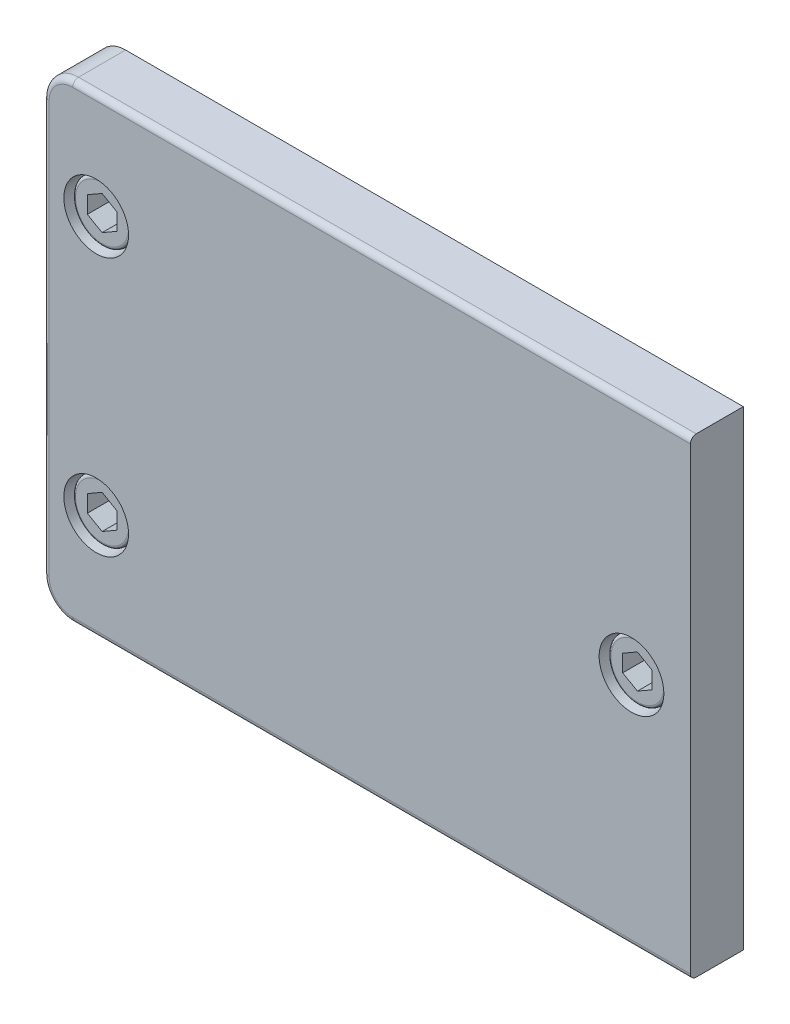
SolidWorks part; units mm, degrees
ref_plane "Plan de face" through (0, 0, 0) normal (0, 0, 1) x (1, 0, 0)
ref_plane "Plan de dessus" through (0, 0, 0) normal (0, 1, 0) x (1, 0, 0)
ref_plane "Plan de droite" through (0, 0, 0) normal (1, 0, 0) x (0, 0, -1)
sketch "Esquisse1" plane through (0, 0, 0) normal (0, 0, 1) x (-1, 0, 0)
  line L8 (0, 5) -> (0, 75)
  line L9 (-5, 80) -> (-110, 80)
  line L10 (-110, 80) -> (-110, 0)
  line L11 (-110, 0) -> (-5, 0)
  arc A4 (0, 75) -> (-5, 80) centre (-5, 75) ccw
  arc A5 (-5, 0) -> (0, 5) centre (-5, 5) ccw
extrude "Boss.-Extru.1" add sketch "Esquisse1" along normal blind 9
fillet "Congé1" radius 1 5 edges at (57.5, -80, 9) (1.4645, -78.5355, 9) (0, -40, 9) (57.5, 0, 9) (1.4645, -1.4645, 9)
sketch "Esquisse2" plane through (0, 0, 0) normal (0, 0, -1) x (1, 0, 0)
  circle A2 centre (9, 18) radius 3.3235
  circle A3 centre (6, 40) radius 3
  circle A4 centre (9, 62) radius 3.3235
  circle A5 centre (50, 40) radius 38
  circle A6 centre (100, 40) radius 3.3235
sketch "Esquisse4" plane through (0, 0, 9) normal (0, 0, 1) x (1, 0, 0)
  circle A0 centre (9, -18) radius 5.5
  dimension "D1" = 11
extrude "Enlèv. mat.-Extru.1" cut sketch "Esquisse4" against normal blind 7
sketch "Esquisse5" plane through (0, 0, 2) normal (0, 0, 1) x (1, 0, 0)
  circle A0 centre (9, -18) radius 5
  dimension "D1" = 10
extrude "Boss.-Extru.2" add sketch "Esquisse5" along normal blind 6
fillet "Congé2" radius 0.5 1 edges at (14, -18, 8)
sketch "Esquisse6" plane through (0, 0, 8) normal (0, 0, 1) x (1, 0, 0)
  line L0 (9, -15.1132) -> (9, -20.8868) construction
  line L1 (9, -15.1132) -> (6.5, -16.5566)
  line L2 (6.5, -16.5566) -> (6.5, -19.4434)
  line L3 (6.5, -19.4434) -> (9, -20.8868)
  line L4 (9, -20.8868) -> (11.5, -19.4434)
  line L5 (11.5, -19.4434) -> (11.5, -16.5566)
  line L6 (11.5, -16.5566) -> (9, -15.1132)
  circle A0 centre (9, -18) radius 2.5 construction
  dimension "D1" = 5
extrude "Enlèv. mat.-Extru.2" cut sketch "Esquisse6" against normal blind 4
pattern_linear "Répétition linéaire1" count 2 spacing 44 along (0, -1, 0) of "Enlèv. mat.-Extru.1", "Boss.-Extru.2", "Congé2", "Enlèv. mat.-Extru.2"
sketch "Esquisse7" plane through (0, 0, 9) normal (0, 0, 1) x (1, 0, 0)
  circle A0 centre (100, -40) radius 5.5
  dimension "D1" = 11
extrude "Enlèv. mat.-Extru.3" cut sketch "Esquisse7" against normal blind 7
sketch "Esquisse8" plane through (0, 0, 2) normal (0, 0, 1) x (1, 0, 0)
  circle A0 centre (100, -40) radius 5
  dimension "D1" = 10
extrude "Boss.-Extru.3" add sketch "Esquisse8" along normal blind 6
fillet "Congé3" radius 0.5 1 edges at (105, -40, 8)
sketch "Esquisse9" plane through (0, 0, 8) normal (0, 0, 1) x (1, 0, 0)
  line L1 (100, -37.1132) -> (97.5, -38.5566)
  line L2 (97.5, -38.5566) -> (97.5, -41.4434)
  line L3 (97.5, -41.4434) -> (100, -42.8868)
  line L4 (100, -42.8868) -> (102.5, -41.4434)
  line L5 (102.5, -41.4434) -> (102.5, -38.5566)
  line L6 (102.5, -38.5566) -> (100, -37.1132)
  circle A0 centre (100, -40) radius 2.5 construction
  dimension "D1" = 5
extrude "Enlèv. mat.-Extru.4" cut sketch "Esquisse9" against normal blind 5
sketch "Esquisse10" plane through (0, 0, 0) normal (0, 0, -1) x (-1, 0, 0)
  circle A0 centre (-6, -40) radius 3
extrude "Enlèv. mat.-Extru.5" cut sketch "Esquisse10" against normal blind 5
sketch "Esquisse11" plane through (0, 0, 9) normal (0, 0, 1) x (1, 0, 0)
  circle A0 centre (50, -40) radius 15
  dimension "D1" = 30
extrude "Enlèv. mat.-Extru.6" [suppressed] cut sketch "Esquisse11" against normal through all
